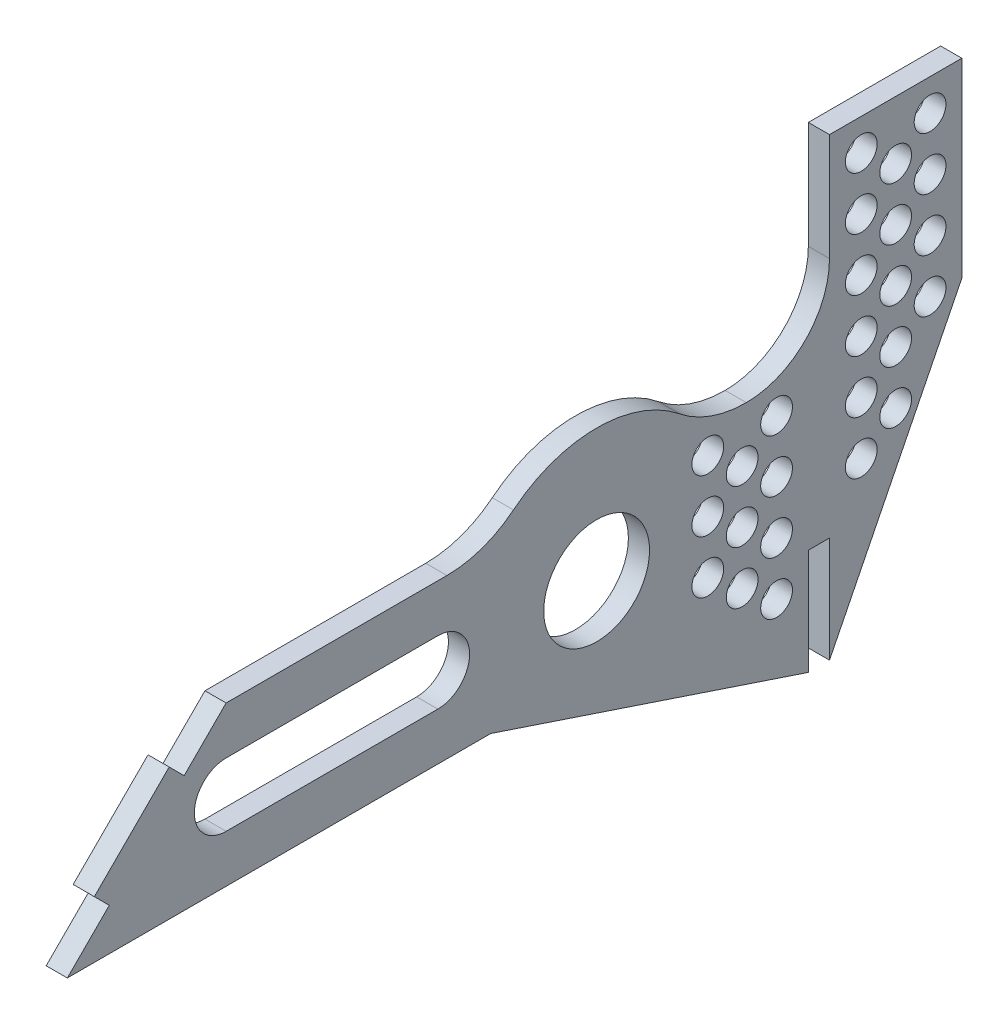
SolidWorks part; units mm, degrees
material "AISI 4340 Steel, normalized"
ref_plane "Front Plane" through (0, 0, 0) normal (0, 0, 1) x (1, 0, 0)
ref_plane "Top Plane" through (0, 0, 0) normal (0, 1, 0) x (1, 0, 0)
ref_plane "Right Plane" through (0, 0, 0) normal (1, 0, 0) x (0, 0, -1)
sketch "Sketch1" plane through (0, 0, 0) normal (1, 0, 0) x (0, 0, -1)
  line B0 (20, 0) -> (-20, 0)
  line B1 (-20, -12) -> (20, -12)
  line B2 (94, 49) -> (94, 24.7157)
  line B3 (21.7157, 9) -> (-20, 9)
  line B4 (-20, 9) -> (-50, -21)
  line B5 (-50, -21) -> (18.1966, -21)
  line B6 (40.5573, -26.2786) -> (90, -51)
  line B7 (90, -51) -> (90, 9)
  line B8 (90, 9) -> (94, 9)
  line B9 (94, 9) -> (94, -51)
  line B10 (94, -51) -> (119, 9)
  line B11 (119, 9) -> (119, 49)
  line B12 (119, 49) -> (94, 49)
  circle B13 centre (50, -6) radius 10
  arc B14 (20, -12) -> (20, 0) centre (20, -6) ccw
  arc B15 (78.2843, 9) -> (94, 24.7157) centre (78.2843, 24.7157) ccw
  arc B16 (65.7135, 13.4444) -> (78.2843, 9) centre (78.2843, 29) ccw
  arc B17 (65.7135, 13.4444) -> (34.2865, 13.4444) centre (50, -6) ccw
  arc B18 (21.7157, 9) -> (34.2865, 13.4444) centre (21.7157, 29) ccw
  arc B19 (40.5573, -26.2786) -> (18.1966, -21) centre (18.1966, -71) ccw
  arc B20 (-20, 0) -> (-20, -12) centre (-20, -6) ccw
  circle B21 centre (106.5, -6) radius 3
  circle B22 centre (106.5, 4) radius 3
  circle B23 centre (113, 9) radius 3
  circle B24 centre (106.5, 14) radius 3
  circle B25 centre (113, 19) radius 3
  circle B26 centre (106.5, 24) radius 3
  circle B27 centre (113, 29) radius 3
  circle B28 centre (113, 39) radius 3
  circle B29 centre (106.5, 34) radius 3
  circle B30 centre (100, 39) radius 3
  circle B31 centre (100, 29) radius 3
  circle B32 centre (100, 19) radius 3
  circle B33 centre (100, 9) radius 3
  circle B34 centre (100, -1) radius 3
  circle B35 centre (100, -11) radius 3
  circle B36 centre (100, -21) radius 3
  circle B37 centre (84, 4) radius 3
  circle B38 centre (84, -6) radius 3
  circle B39 centre (77.5, -1) radius 3
  circle B40 centre (71, 4) radius 3
  circle B41 centre (71, -6) radius 3
  circle B42 centre (77.5, -11) radius 3
  circle B43 centre (84, -16) radius 3
  circle B44 centre (71, -16) radius 3
  circle B45 centre (77.5, -21) radius 3
  circle B46 centre (84, -26) radius 3
  circle B47 centre (84, -36) radius 3
  circle B48 centre (77.5, -31) radius 3
  circle B49 centre (71, -26) radius 3
sketch_block_instance "Block-pedalbox side-1"
sketch_block "Block1"
sketch "Sketch2" plane through (0, 0, 0) normal (1, 0, 0) x (0, 0, -1)
  line L1 (119, 9) -> (119, 49) construction
  line L2 (94, 49) -> (94, 24.7157) construction
  line L3 (21.7157, 9) -> (-20, 9) construction
  line L4 (20, 0) -> (-20, 0) construction
  line L5 (-20, -12) -> (20, -12) construction
  line L6 (-50, -21) -> (18.1966, -21) construction
  line L7 (-20, 9) -> (-50, -21) construction
  line L9 (119, 9) -> (119, 44.9957)
  line L10 (94, 44.9957) -> (94, 24.7157)
  line L11 (21.7157, 9) -> (-20, 9)
  line L12 (20, 0) -> (-20, 0)
  line L13 (-20, -12) -> (20, -12)
  line L14 (-50, -21) -> (18.1966, -21)
  line L15 (-20, 9) -> (-27.9289, 1.0711)
  line L16 (94, 44.9957) -> (119, 44.9957)
  line L17 (90, -21) -> (94, -21)
  line L18 (90, -51) -> (90, 9) construction
  line L19 (94, 9) -> (94, -51) construction
  line L20 (90, 9) -> (94, 9) construction
  line L22 (30, -21) -> (90, -41)
  line L23 (18.1966, -21) -> (30, -21)
  line L24 (90, -41) -> (90, -21)
  line L25 (94, -21) -> (94, -41)
  line L26 (94, -41) -> (119, 9)
  line L27 (-35, -6) -> (-42.9011, 1.9011) construction
  line L28 (-27.9289, 1.0711) -> (-30.7574, 3.8995)
  line L29 (-30.7574, 3.8995) -> (-44.8995, -10.2426)
  line L30 (-44.8995, -10.2426) -> (-42.0711, -13.0711)
  line L31 (-42.0711, -13.0711) -> (-50, -21)
  line L32 (-42.0711, -13.0711) -> (-27.9289, 1.0711) construction
  arc A0 (78.2843, 9) -> (94, 24.7157) centre (78.2843, 24.7157) ccw construction
  arc A1 (65.7135, 13.4444) -> (78.2843, 9) centre (78.2843, 29) ccw construction
  arc A2 (65.7135, 13.4444) -> (34.2865, 13.4444) centre (50, -6) ccw construction
  arc A3 (21.7157, 9) -> (34.2865, 13.4444) centre (21.7157, 29) ccw construction
  arc A4 (20, -12) -> (20, 0) centre (20, -6) ccw construction
  arc A5 (-20, 0) -> (-20, -12) centre (-20, -6) ccw construction
  arc A6 (78.2843, 9) -> (94, 24.7157) centre (78.2843, 24.7157) ccw
  arc A7 (65.7135, 13.4444) -> (78.2843, 9) centre (78.2843, 29) ccw
  arc A8 (65.7135, 13.4444) -> (34.2865, 13.4444) centre (50, -6) ccw
  arc A9 (21.7157, 9) -> (34.2865, 13.4444) centre (21.7157, 29) ccw
  arc A10 (20, -12) -> (20, 0) centre (20, -6) ccw
  arc A11 (-20, 0) -> (-20, -12) centre (-20, -6) ccw
  circle A12 centre (50, -6) radius 10 construction
  circle A13 centre (50, -6) radius 10
  circle A14 centre (84, -26) radius 3 construction
  circle A15 centre (106.5, -6) radius 3 construction
  circle A16 centre (106.5, 4) radius 3 construction
  circle A17 centre (113, 9) radius 3 construction
  circle A18 centre (106.5, 14) radius 3 construction
  circle A19 centre (113, 19) radius 3 construction
  circle A20 centre (106.5, 24) radius 3 construction
  circle A21 centre (113, 29) radius 3 construction
  circle A22 centre (113, 39) radius 3 construction
  circle A23 centre (106.5, 34) radius 3 construction
  circle A24 centre (100, 39) radius 3 construction
  circle A25 centre (100, 29) radius 3 construction
  circle A26 centre (100, 19) radius 3 construction
  circle A27 centre (100, 9) radius 3 construction
  circle A28 centre (100, -1) radius 3 construction
  circle A29 centre (100, -11) radius 3 construction
  circle A30 centre (84, 4) radius 3 construction
  circle A31 centre (71, 4) radius 3 construction
  circle A32 centre (77.5, -1) radius 3 construction
  circle A33 centre (84, -6) radius 3 construction
  circle A34 centre (84, -16) radius 3 construction
  circle A35 centre (77.5, -11) radius 3 construction
  circle A36 centre (71, -6) radius 3 construction
  circle A37 centre (71, -16) radius 3 construction
  circle A38 centre (77.5, -21) radius 3 construction
  circle A39 centre (106.5, -6) radius 3
  circle A40 centre (106.5, 4) radius 3
  circle A41 centre (113, 9) radius 3
  circle A42 centre (106.5, 14) radius 3
  circle A43 centre (113, 19) radius 3
  circle A44 centre (106.5, 24) radius 3
  circle A45 centre (113, 29) radius 3
  circle A46 centre (113, 39) radius 3
  circle A47 centre (106.5, 34) radius 3
  circle A48 centre (100, 39) radius 3
  circle A49 centre (100, 29) radius 3
  circle A50 centre (100, 19) radius 3
  circle A51 centre (100, 9) radius 3
  circle A52 centre (100, -1) radius 3
  circle A53 centre (100, -11) radius 3
  circle A54 centre (84, 4) radius 3
  circle A55 centre (71, 4) radius 3
  circle A56 centre (77.5, -1) radius 3
  circle A57 centre (84, -6) radius 3
  circle A58 centre (84, -16) radius 3
  circle A59 centre (77.5, -11) radius 3
  circle A60 centre (71, -6) radius 3
  circle A61 centre (71, -16) radius 3
  circle A62 centre (84, -26) radius 3
  circle A63 centre (77.5, -21) radius 3
  dimension "D1" = 20.28
  dimension "D2" = 30
  dimension "D3" = 20
  dimension "D4" = 60
  dimension "D5" = 4
  dimension "D6" = 20
extrude "Boss-Extrude1" add sketch "Sketch2" along normal blind 4
